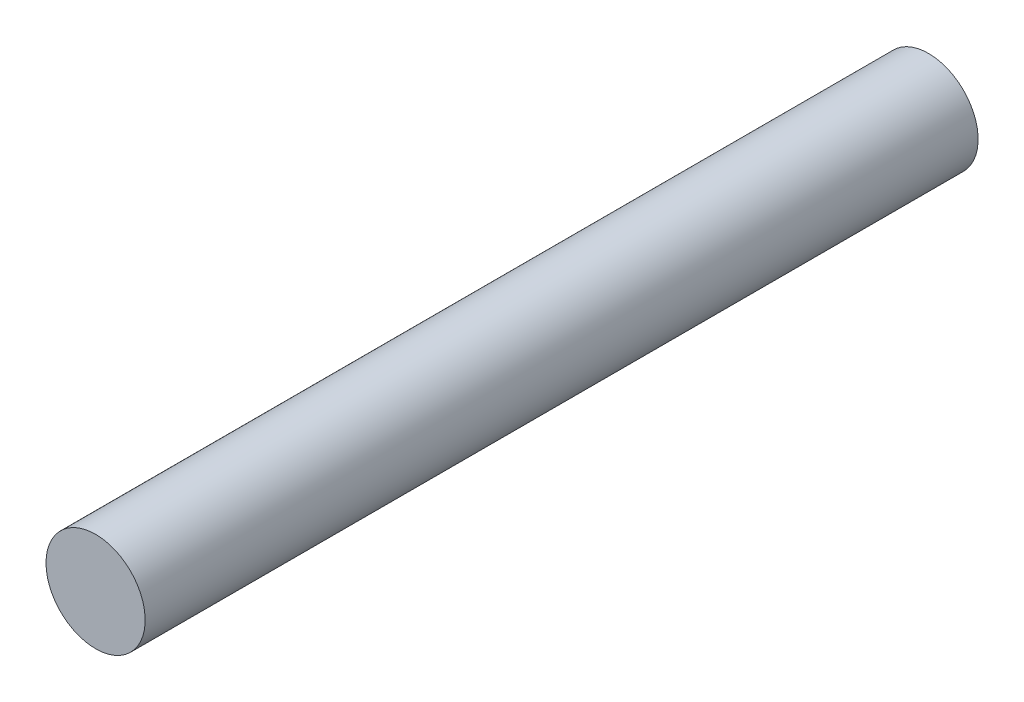
SolidWorks part; units mm, degrees
ref_plane "Front Plane" through (0, 0, 0) normal (0, 0, 1) x (1, 0, 0)
ref_plane "Top Plane" through (0, 0, 0) normal (0, 1, 0) x (1, 0, 0)
ref_plane "Right Plane" through (0, 0, 0) normal (1, 0, 0) x (0, 0, -1)
sketch "Sketch1" plane through (0, 0, 0) normal (0, 0, 1) x (1, 0, 0)
  circle A0 centre (0, 0) radius 2.5
extrude "Boss-Extrude1" add sketch "Sketch1" along normal blind 42
